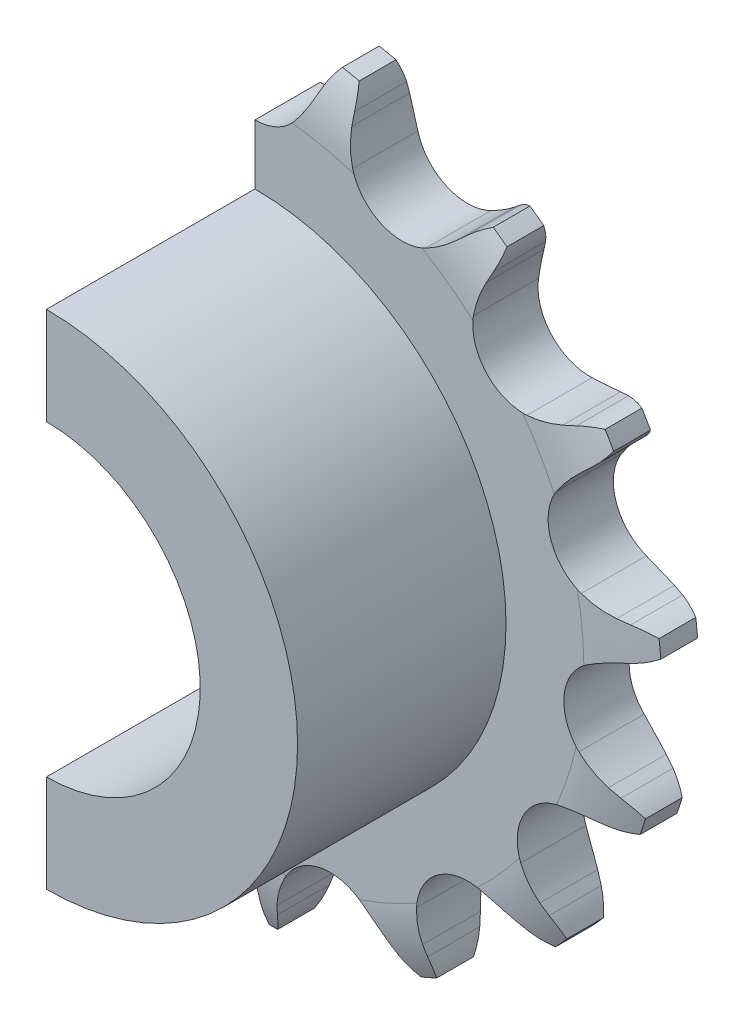
SolidWorks part; units mm, degrees
ref_plane "Front Plane" through (0, 0, 0) normal (0, 0, 1) x (1, 0, 0)
ref_plane "Top Plane" through (0, 0, 0) normal (0, 1, 0) x (1, 0, 0)
ref_plane "Right Plane" through (0, 0, 0) normal (1, 0, 0) x (0, 0, -1)
sketch "Sketch0" plane through (0, 0, 0) normal (0, 0, 1) x (1, 0, 0)
  line L0 (3, -14.1139) -> (0, 0) construction
  line L1 (0, 0) -> (8.4813, -11.6735) construction
  line L2 (0, 0) -> (-3, -14.1139) construction
  line L3 (3, -14.1139) -> (8.4813, -11.6735) construction
  line L4 (3, -14.1139) -> (-3, -14.1139) construction
  line L5 (5.4587, -13.8191) -> (5.1921, -13.4619)
  line L6 (3, -14.1139) -> (0, -14.7516) construction
  line L7 (0.6339, -14.8447) -> (0.7322, -14.4099)
  line L8 (0, -14.1139) -> (0, -15.9139) construction
  line L9 (4.2889, -12.5222) -> (0.9862, -16.6008) construction
  line L10 (0, 0) -> (0, -14.1139) construction
  line L11 (5.1921, -13.4619) -> (0.9862, -16.6008) construction
  line L12 (0, -15.9139) -> (0, -16.1712) construction
  line L13 (8.1159, -11.8362) -> (5.4587, -13.8191) construction
  circle A0 centre (0, 0) radius 15.9139 construction
  circle A1 centre (0, 0) radius 14.4292 construction
  arc A2 (-3.2007, -17.3745) -> (9.9908, -14.5706) centre (0, 0) ccw
  circle A3 centre (0, 0) radius 16.1712 construction
  circle A4 centre (3, -14.1139) radius 2 construction
  arc A7 (4.2889, -12.5222) -> (1.1751, -13.1841) centre (3, -14.1139) ccw
  circle A8 centre (3, -14.1139) radius 2.0481 construction
  arc A9 (5.4587, -13.8191) -> (9.9908, -14.5706) centre (8.1159, -11.8362) ccw
  arc A10 (5.1921, -13.4619) -> (4.2889, -12.5222) centre (0.9862, -16.6008) ccw
  arc A11 (0.6339, -14.8447) -> (-3.2007, -17.3745) centre (-2.6, -14.1139) cw
  arc A12 (0.7322, -14.4099) -> (1.1751, -13.1841) centre (5.8512, -15.5667) cw
  dimension "D1" = 2.0481
  dimension "R" = 2.0481
sketch "Sketch1" plane through (0, 0, 0) normal (1, 0, 0) x (0, 0, -1)
  line L0 (1.3, 0) -> (-1.3, 0)
  line L1 (-1.3, 0) -> (-1.3, 13.1014)
  line L2 (-1.3, 14.4292) -> (0, 14.4292) construction
  line L3 (-0.6, 15.9139) -> (0.6, 15.9139)
  line L5 (1.3, 13.1014) -> (1.3, 0)
  line L7 (0, 15.9139) -> (0, 0) construction
  line L8 (-1.3, 13.1014) -> (1.3, 13.1014) construction
  line L9 (0, 15.9139) -> (0, -15.9139) construction
  line L10 (-1.3, 13.1014) -> (-1.3, 15.9139) construction
  line L11 (-1.3, 15.9139) -> (-0.6, 15.9139) construction
  line L12 (0.6, 15.9139) -> (1.3, 15.9139) construction
  line L13 (1.3, 15.9139) -> (1.3, 13.1014) construction
  line L14 (0, 0) -> (-6.4008, 0) construction
  line L15 (-1.3, 14.4292) -> (-1.3, 10.3292) construction
  line L22 (1.3, 0) -> (-8.7, 0) construction
  line L24 (-1.3, 0) -> (-1.3, 10.3292) construction
  arc A0 (-0.6, 15.9139) -> (-1.3, 13.1014) centre (4.7, 13.1014) ccw
  arc A1 (0.6, 15.9139) -> (1.3, 13.1014) centre (-4.7, 13.1014) cw
  dimension "R" = 6
revolve "Revolve1" add sketch "Sketch1" angle 360 mid plane about L0
extrude "Cut-Extrude1" cut sketch "Sketch0" against normal through all and the other way through all
pattern_circular "CirPattern1" count 15 over 360 about axis through (0, 0, 0) along (0, 0, 1) of "Cut-Extrude1"
sketch "Sketch2" plane through (0, 0, 0) normal (0, 0, 1) x (1, 0, 0)
  circle A0 centre (0, 0) radius 3 construction
  circle A1 centre (0, 0) radius 10
  circle A2 centre (0, 0) radius 15.65 construction
  dimension "Bore" = 6
  dimension "Hub Dia." = 20
  dimension "OD" = 31.3
extrude "Boss-Extrude1" add sketch "Sketch2" along normal up to vertex (8.7 mm away) from surface at 1.3 starting at face at (0, 0, 1.3)
sketch "Sketch3" plane through (0, 0, 0) normal (0, 0, 1) x (1, 0, 0)
  circle A0 centre (0, 0) radius 3 construction
  circle A1 centre (0, 0) radius 3
extrude "Cut-Extrude2" cut sketch "Sketch3" along normal through all and the other way through all
sketch "Sketch4" plane through (0, 0, 0) normal (1, 0, 0) x (0, 0, -1)
  line L0 (-8.7, 10) -> (-8.7, 9.5)
  line L1 (-1.3, 15.9139) -> (-3.25, 15.9139)
  line L2 (-1.3, 15.9139) -> (-1.3, 10.3292)
  line L3 (-1.3, 10.3292) -> (-3.25, 10.3292)
  line L4 (-3.25, 15.9139) -> (-3.25, 10.3292)
  line L9 (-8.7, 9.5) -> (-8.2, 10)
  line L10 (-8.2, 10) -> (-8.7, 10)
  dimension "C" = 0.5
  dimension "D3" = 1.95
revolve "Cut-Revolve1" cut sketch "Sketch4" angle 360 mid plane about L22
sketch "Sketch5" plane through (0, 0, 0) normal (0, 0, 1) x (1, 0, 0)
  circle A0 centre (0, 0) radius 15.65 construction
  circle A1 centre (0, 0) radius 15.65
extrude "Cut-Extrude3" cut sketch "Sketch5" against normal through all and the other way through all flip side to cut
sketch "Sketch6" plane through (0, 0, 0) normal (0, 0, 1) x (1, 0, 0)
  circle A0 centre (0, 0) radius 10
  dimension "D1" = 20
extrude "Cut-Extrude4" cut sketch "Sketch6" against normal through all both and the other way through all
sketch "Sketch7" plane through (0, 0, 1.3) normal (0, 0, 1) x (1, 0, 0)
  circle A0 centre (0, 0) radius 10
  circle A2 centre (0, 0) radius 6.125
  dimension "D1" = 20
  dimension "D2" = 12.25
extrude "Boss-Extrude2" add sketch "Sketch7" along normal blind 8.3 and the other way up to surface (2.6 mm away) other way up to face at (0, 10, -1.3)
sketch "Sketch8" plane through (0, 0, 0) normal (0, 0, 1) x (1, 0, 0)
  line L0 (0, 20.8664) -> (0, -21.8881) construction
  line L2 (0, 18.377) -> (-18.3778, 18.377)
  line L3 (0, 18.377) -> (0, -18.0918)
  line L4 (0, -18.0918) -> (-18.3778, -18.0918)
  line L5 (-18.3778, 18.377) -> (-18.3778, -18.0918)
extrude "Cut-Extrude5" cut sketch "Sketch8" against normal through all both and the other way through all
equation "\"360/N@Sketch0\" = 360/\"Teeth@CirPattern1\""
equation "\"Ds@Sketch0\" = 1.005 * \"Dr@Sketch0\" + ( 0.003 * 25.4 ) "
equation "\"R@Sketch0\" = 1/2 * \"Ds@Sketch0\""
equation "\"A@Sketch0\" = 35 +  ( 60 / \"Teeth@CirPattern1\" ) "
equation "\"B@Sketch0\" = 18 -  ( 56 / \"Teeth@CirPattern1\" )"
equation "\"ac@Sketch0\" = 0.8 * \"Dr@Sketch0\""
equation "\"ab@Sketch0\" = 1.4 * \"Dr@Sketch0\""
equation "\"J@Sketch0\" = 0.3 * \"Pitch@Sketch0\""
equation "\"D3@Sketch4\" = \"t@Sketch1\" * 3 / 4"
